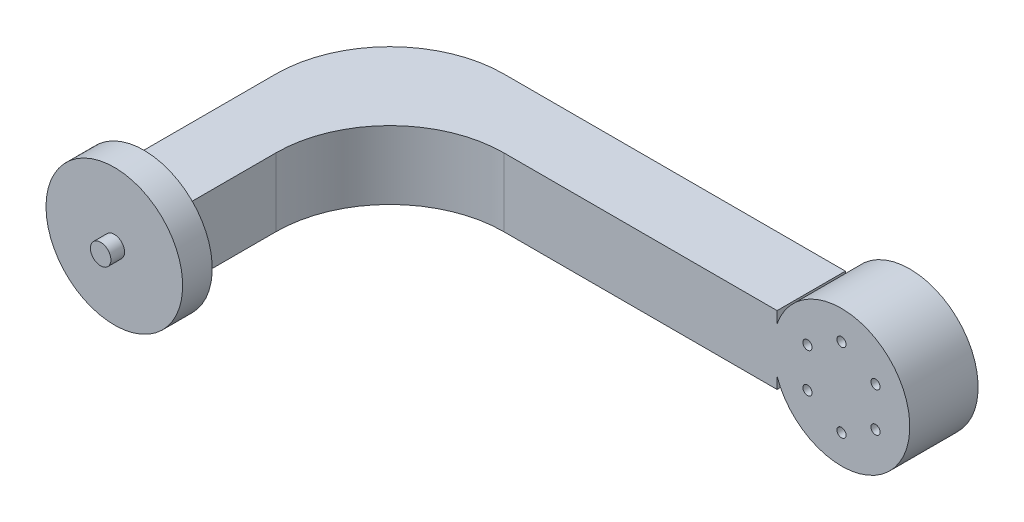
SolidWorks part; units mm, degrees
ref_plane "前视基准面" through (0, 0, 0) normal (0, 0, 1) x (1, 0, 0)
ref_plane "上视基准面" through (0, 0, 0) normal (0, 1, 0) x (1, 0, 0)
ref_plane "右视基准面" through (0, 0, 0) normal (1, 0, 0) x (0, 0, -1)
other "Configuration Table"
sketch "草图1" plane through (0, 0, 0) normal (0, 0, 1) x (1, 0, 0)
  line L0 (100, 0) -> (100, 10)
  line L1 (-100, 15) -> (100, 15)
  line L2 (-100, 15) -> (-100, -15)
  line L3 (-100, -15) -> (100, -15)
  line L4 (100, 15) -> (100, -15)
  line L5 (-100, 15) -> (100, -15) construction
  line L6 (-100, -15) -> (100, 15) construction
  line L7 (100, 0) -> (100, -10)
  arc A0 (100, 10) -> (100, -10) centre (128.2843, 0) cw
  point P0 (0, 0)
  dimension "D1" = 200
  dimension "D2" = 30
extrude "凸台-拉伸1" add sketch "草图1" along normal blind 30 contours L4 L1 L2 L3 L0 | A0 L0 L4
sketch "草图12" plane through (0, 15, 0) normal (0, 1, 0) x (1, 0, 0)
  line L0 (-100, -30) -> (-100, -123)
  line L1 (-49.331, 0) -> (-70, 0)
  line L2 (-33, 0) -> (33, 0) construction
  line L3 (-70, 0) -> (-70, -123)
  line L4 (-70, -123) -> (-100, -123)
  line L5 (-100, 0) -> (-100, -30)
  line M4 (-100, -30) -> (100, -30)
extrude "凸台-拉伸6" add sketch "草图12" against normal up to surface (30 mm away) contours L4 L3 L0 M4 up to face at (0, -15, 15)
sketch "草图16" plane through (0, 0, 123) normal (0, 0, 1) x (1, 0, 0)
  line L1 (16.5, 0) -> (-16.5, 0) construction
  circle A1 centre (-85, 0) radius 30
extrude "凸台-拉伸9" add sketch "草图16" along normal blind 13
fillet "圆角1" radius 50 1 edges at (-70, 0, 30)
fillet "圆角2" radius 50 1 edges at (-100, 0, 0)
sketch "草图17" plane through (0, 0, 30) normal (0, 0, 1) x (1, 0, 0)
  circle A1 centre (128.2843, 17.25) radius 2
extrude "切除-拉伸1" cut sketch "草图17" against normal through all
pattern_circular "阵列(圆周)1" count 6 over 360 about axis through (128.2843, 0, 0) along (0, 0, 1) of "切除-拉伸1"
sketch "草图18" plane through (0, 0, 136) normal (0, 0, 1) x (1, 0, 0)
  circle A0 centre (-85, 0) radius 4.5
extrude "凸台-拉伸10" add sketch "草图18" along normal blind 6
